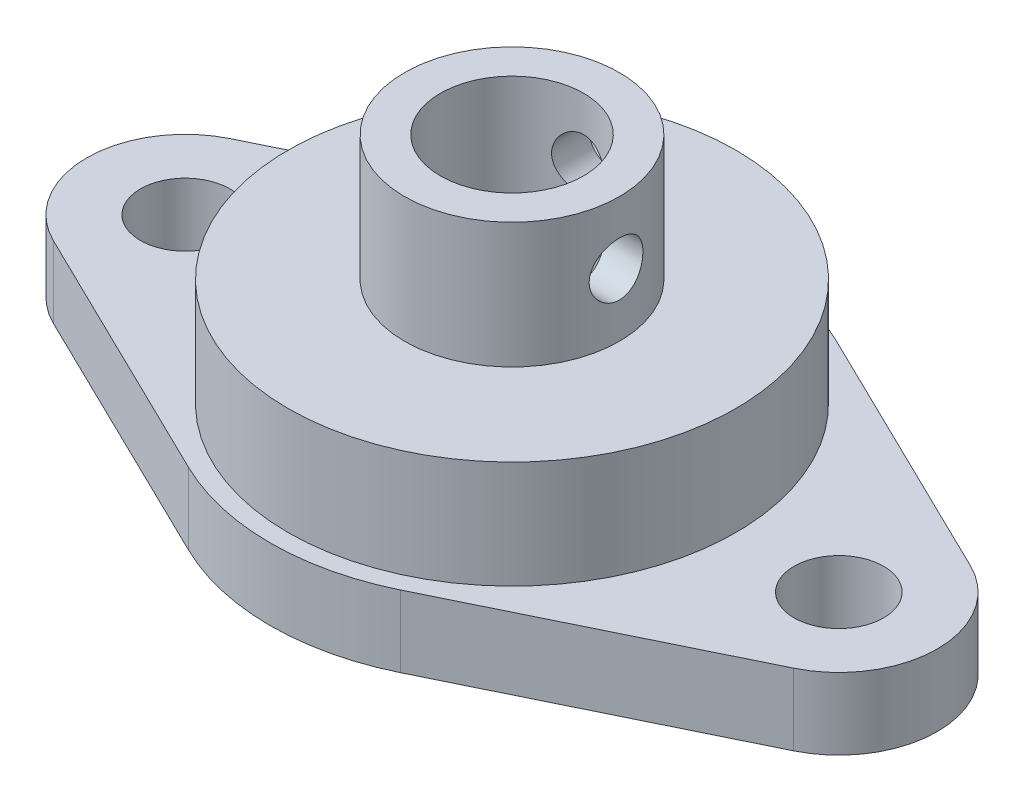
SolidWorks part; units mm, degrees
ref_plane "Front Plane" through (0, 0, 0) normal (0, 0, 1) x (1, 0, 0)
ref_plane "Top Plane" through (0, 0, 0) normal (0, 1, 0) x (1, 0, 0)
ref_plane "Right Plane" through (0, 0, 0) normal (1, 0, 0) x (0, 0, -1)
sketch "Sketch1" plane through (0, 0, 0) normal (0, 1, 0) x (1, 0, 0)
  line L0 (0, 0) -> (32.6833, 0) construction
  line L1 (0, 0) -> (0, 21.0253) construction
  line L2 (-20.661, 4.9434) -> (-5.9178, 12.1338)
  line L3 (-20.661, -4.9434) -> (-5.9178, -12.1338)
  line L4 (20.661, 4.9434) -> (5.9178, 12.1338)
  line L5 (20.661, -4.9434) -> (5.9178, -12.1338)
  arc A0 (-5.9178, -12.1338) -> (5.9178, -12.1338) centre (0, 0) ccw
  circle A2 centre (18.25, 0) radius 2.5
  circle A3 centre (-18.25, 0) radius 2.5
  arc A4 (-20.661, 4.9434) -> (-20.661, -4.9434) centre (-18.25, 0) ccw
  arc A5 (20.661, -4.9434) -> (20.661, 4.9434) centre (18.25, 0) ccw
  arc A6 (5.9178, 12.1338) -> (-5.9178, 12.1338) centre (0, 0) ccw
  circle A7 centre (0, 0) radius 4
  dimension "D1" = 27
  dimension "D2" = 5
  dimension "D3" = 36.5
  dimension "D4" = 11
  dimension "D5" = 8
extrude "Boss-Extrude1" add sketch "Sketch1" along normal blind 4
sketch "Sketch2" plane through (0, 4, 0) normal (0, 1, 0) x (1, 0, 0)
  circle A0 centre (0, 0) radius 12.5
  circle A1 centre (0, 0) radius 4
  dimension "D1" = 25
extrude "Boss-Extrude2" add sketch "Sketch2" along normal blind 6
sketch "Sketch3" plane through (0, 10, 0) normal (0, 1, 0) x (1, 0, 0)
  circle A0 centre (0, 0) radius 4
  circle A1 centre (0, 0) radius 6
  dimension "D1" = 8
  dimension "D2" = 12
extrude "Boss-Extrude3" add sketch "Sketch3" along normal blind 7
sketch "Sketch4" plane through (0, 0, 0) normal (0, 0, 1) x (1, 0, 0)
  line L0 (0, 0) -> (0, 13.5) construction
  circle A0 centre (0, 13.5) radius 1.5
  dimension "D2" = 3
  dimension "D1" = 13.5
extrude "Cut-Extrude1" cut sketch "Sketch4" against normal through all
ref_plane "Plane1" through (0, 0, 0) normal (0.7071, 0, 0.7071) x (0.7071, 0, -0.7071)
mirror "Mirror1" about plane through (0, 0, 0) normal (0.7071, 0, 0.7071) of "Cut-Extrude1"
sketch "Sketch5" plane through (0, 10, 0) normal (0, 1, 0) x (1, 0, 0)
  circle A0 centre (0, 0) radius 6
  circle A1 centre (0, 0) radius 10.5
  dimension "D1" = 21
  dimension "D2" = 12
